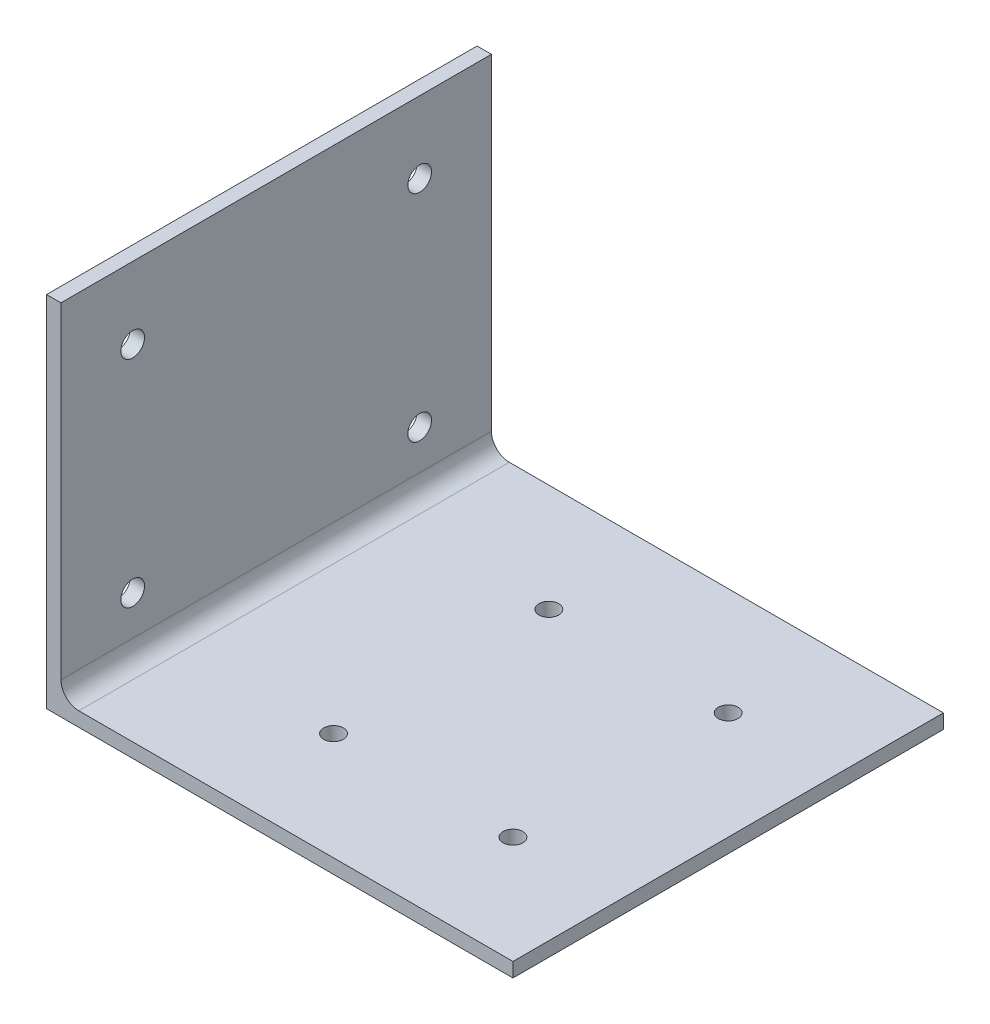
SolidWorks part; units mm, degrees
material "6061-T6 (SS)"
ref_plane "Front Plane" through (0, 0, 0) normal (0, 0, 1) x (1, 0, 0)
ref_plane "Top Plane" through (0, 0, 0) normal (0, 1, 0) x (1, 0, 0)
ref_plane "Right Plane" through (0, 0, 0) normal (1, 0, 0) x (0, 0, -1)
sketch "Sketch2" plane through (0, 0, 0) normal (0, 0, 1) x (1, 0, 0)
  line L0 (0, 0) -> (0, 100)
  line L1 (0, 100) -> (4, 100)
  line L2 (4, 100) -> (4, 4)
  line L3 (4, 4) -> (130, 4)
  line L4 (130, 4) -> (130, 0)
  line L5 (130, 0) -> (0, 0)
  dimension "D1" = 100
  dimension "D2" = 4
  dimension "D3" = 4
  dimension "D4" = 130
extrude "Boss-Extrude1" add sketch "Sketch2" along normal blind 120
sketch "Sketch4" plane through (4, 0, 0) normal (1, 0, 0) x (0, 0, -1)
  line L0 (0, 4) -> (0, 100) construction
  line L1 (-120, 100) -> (0, 100) construction
  circle A0 centre (-100, 80) radius 3.3
  circle A1 centre (-20, 80) radius 3.3
  circle A2 centre (-20, 20) radius 3.3
  circle A3 centre (-100, 20) radius 3.3
  point P8 (0, 0)
  point P9 (0, 0)
  point P10 (0, 0)
  dimension "D1" = 6.6
  dimension "D2" = 60
  dimension "D3" = 80
  dimension "D4" = 20
  dimension "D5" = 20
extrude "Cut-Extrude1" cut sketch "Sketch4" against normal through all
sketch "Sketch5" plane through (0, 4, 0) normal (0, 1, 0) x (1, 0, 0)
  line L0 (0, -120) -> (0, 0) construction
  line L1 (130, -120) -> (4, -120) construction
  circle A0 centre (100, -30) radius 2.75
  circle A1 centre (50, -30) radius 2.75
  circle A2 centre (50, -90) radius 2.75
  circle A3 centre (100, -90) radius 2.75
  point P8 (0, 0)
  point P9 (0, 0)
  point P10 (0, 0)
  dimension "D1" = 5.5
  dimension "D2" = 50
  dimension "D3" = 60
  dimension "D4" = 50
  dimension "D5" = 30
extrude "Cut-Extrude2" cut sketch "Sketch5" against normal through all
fillet "Fillet1" radius 5 1 edges at (4, 4, 60)
